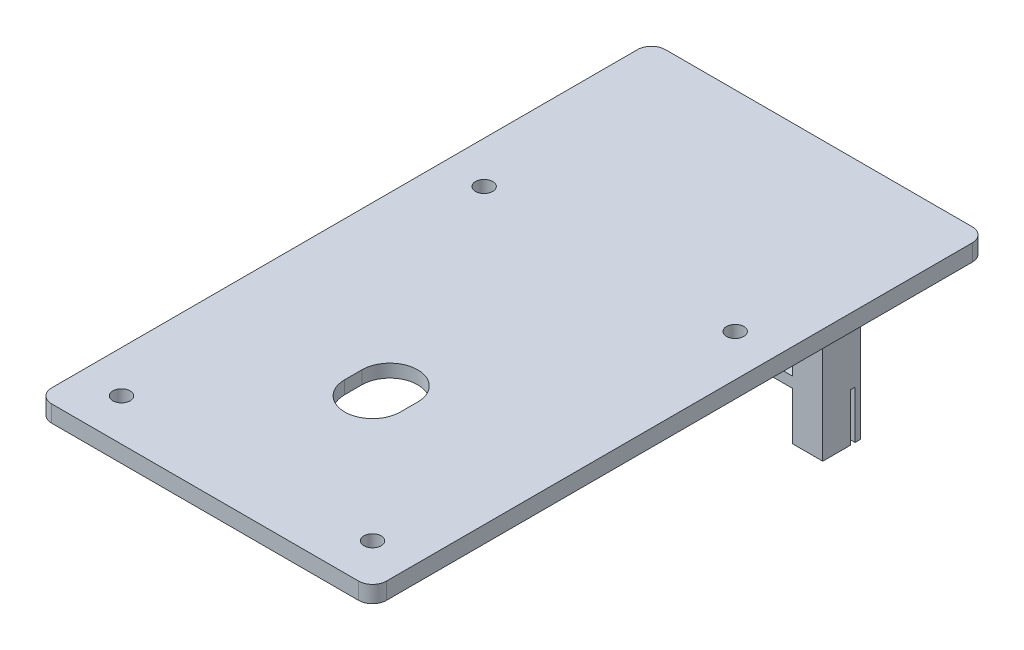
SolidWorks part; units mm, degrees
ref_plane "Front Plane" through (0, 0, 0) normal (0, 0, 1) x (1, 0, 0)
ref_plane "Top Plane" through (0, 0, 0) normal (0, 1, 0) x (1, 0, 0)
ref_plane "Right Plane" through (0, 0, 0) normal (1, 0, 0) x (0, 0, -1)
sketch "Sketch1" plane through (0, 0, 0) normal (0, 1, 0) x (1, 0, 0)
  line L1 (0, 0) -> (60, 0)
  line L2 (0, 0) -> (0, 110)
  line L3 (0, 110) -> (60, 110)
  line L4 (60, 0) -> (60, 110)
  dimension "D1" = 60
  dimension "D2" = 110
extrude "Boss-Extrude1" add sketch "Sketch1" along normal blind 3
sketch "Sketch2" plane through (0, 3, 0) normal (0, 1, 0) x (1, 0, 0)
  line L0 (60, 110) -> (0, 110) construction
  line L1 (0, 110) -> (0, 0) construction
  line L2 (60, 0) -> (60, 110) construction
  line L3 (0, 0) -> (60, 0) construction
  circle A0 centre (7.5, 7.5) radius 1.55
  circle A1 centre (52.5, 7.5) radius 1.55
  circle A2 centre (7.5, 72.5) radius 1.55
  circle A3 centre (52.5, 72.5) radius 1.55
  dimension "D1" = 3.1
  dimension "D2" = 3.1
  dimension "D3" = 3.1
  dimension "D4" = 3.1
  dimension "D5" = 37.5
  dimension "D7" = 37.5
  dimension "D8" = 7.5
  dimension "D9" = 7.5
  dimension "D10" = 7.5
  dimension "D11" = 7.5
  dimension "D12" = 7.5
  dimension "D6" = 7.5
extrude "Cut-Extrude1" cut sketch "Sketch2" against normal blind 3
sketch "Sketch3" plane through (0, 3, 0) normal (0, 1, 0) x (1, 0, 0)
  line L0 (30, 33.1) -> (30, 30) construction
  line L1 (35, 33.1) -> (35, 30)
  line L2 (25, 33.1) -> (25, 30)
  line L3 (0, 110) -> (0, 0) construction
  line L4 (0, 0) -> (60, 0) construction
  arc A0 (35, 33.1) -> (25, 33.1) centre (30, 33.1) ccw
  arc A1 (25, 30) -> (35, 30) centre (30, 30) ccw
  point P2 (30, 31.55)
  point P9 (0, 0)
  dimension "D2" = 5
  dimension "D1" = 3.1
  dimension "D3" = 25
  dimension "D4" = 30
extrude "Cut-Extrude2" cut sketch "Sketch3" against normal blind 2.33
sketch "Sketch4" plane through (0, 0, 0) normal (0, -1, 0) x (1, 0, 0)
  line L0 (26.98, -20.0513) -> (33.02, -20.0513)
  line L1 (40.32, -27.3513) -> (40.32, -35.65)
  line L2 (33.02, -42.95) -> (26.98, -42.9307)
  line L3 (19.68, -27.3513) -> (19.7034, -35.6513)
  line L4 (35, -30) -> (35, -33.1) construction
  arc A0 (33.02, -20.0513) -> (40.32, -27.3513) centre (33.02, -27.3513) cw
  arc A1 (40.32, -35.65) -> (33.02, -42.95) centre (33.02, -35.65) cw
  arc A2 (26.98, -20.0513) -> (19.68, -27.3513) centre (26.98, -27.3513) ccw
  arc A3 (19.7034, -35.6513) -> (26.98, -42.9307) centre (27.0034, -35.6307) ccw
  dimension "D2" = 7.3
  dimension "D6" = 7.3
  dimension "D9" = 7.3
  dimension "D12" = 7.3
  dimension "D1" = 6.04
  dimension "D3" = 0
  dimension "D4" = 0
  dimension "D7" = 0
  dimension "D8" = 0
  dimension "D10" = 0
  dimension "D11" = 0
  dimension "D13" = 6.04
  dimension "D14" = 8.3
  dimension "D15" = 5.32
  dimension "D16" = 2.55
  dimension "D17" = 2.6487
extrude "Cut-Extrude3" cut sketch "Sketch4" against normal up to vertex (0.67 mm away)
sketch "Sketch5" plane through (0, 0, 0) normal (0, -1, 0) x (1, 0, 0)
  line L0 (0, -110) -> (0, 0) construction
  line L1 (60, 0) -> (60, -110) construction
  line L2 (60, -110) -> (0, -110) construction
  circle A0 centre (20.05, -102.5) radius 1.375
  circle A1 centre (39.95, -102.5) radius 1.375
  circle A2 centre (39.95, -76.3) radius 1.375
  circle A3 centre (20.05, -76.3) radius 1.375
  dimension "D1" = 2.75
  dimension "D2" = 2.75
  dimension "D3" = 2.75
  dimension "D4" = 2.75
  dimension "D5" = 0
  dimension "D6" = 19.9
  dimension "D7" = 0
  dimension "D8" = 19.9
  dimension "D9" = 0
  dimension "D10" = 26.2
  dimension "D11" = 20.05
  dimension "D12" = 20.05
  dimension "D13" = 7.5
sketch "Sketch6" plane through (0, 0, 0) normal (0, -1, 0) x (1, 0, 0)
  line L0 (51.3, -93.2) -> (52.5, -93.2)
  line L2 (48.3, -93.2) -> (48.3, -94)
  line L4 (51.3, -93.2) -> (51.3, -94)
  line L5 (52.5, -94) -> (51.3, -94)
  line L6 (52.5, -94) -> (52.5, -95)
  line L7 (52.5, -95) -> (47.1, -95)
  line L8 (47.1, -94) -> (47.1, -95)
  line L9 (47.1, -88.2) -> (52.5, -88.2)
  line L10 (47.1, -88.2) -> (47.1, -93.2)
  line L11 (47.1, -93.2) -> (48.3, -93.2)
  line L12 (52.5, -88.2) -> (52.5, -93.2)
  line L13 (48.3, -94) -> (47.1, -94)
  line L14 (60, 0) -> (60, -110) construction
  line L15 (11.7, -93.2) -> (12.9, -93.2)
  line L16 (8.7, -93.2) -> (8.7, -94)
  line L17 (11.7, -93.2) -> (11.7, -94)
  line L18 (12.9, -94) -> (11.7, -94)
  line L19 (12.9, -94) -> (12.9, -95)
  line L20 (12.9, -95) -> (7.5, -95)
  line L21 (7.5, -94) -> (7.5, -95)
  line L22 (7.5, -88.2) -> (12.9, -88.2)
  line L23 (7.5, -88.2) -> (7.5, -93.2)
  line L24 (7.5, -93.2) -> (8.7, -93.2)
  line L25 (12.9, -88.2) -> (12.9, -93.2)
  line L26 (8.7, -94) -> (7.5, -94)
  line L27 (0, -110) -> (0, 0) construction
  line L28 (60, -110) -> (0, -110) construction
  dimension "D11" = 3
  dimension "D1" = 3
  dimension "D2" = 1.2
  dimension "D3" = 1.2
  dimension "D4" = 1
  dimension "D5" = 0.8
  dimension "D6" = 5
  dimension "D7" = 7.5
  dimension "D8" = 5.4
  dimension "D9" = 3
  dimension "D10" = 5.4
  dimension "D12" = 1.2
  dimension "D13" = 0.8
  dimension "D14" = 5
  dimension "D15" = 5.4
  dimension "D16" = 3
  dimension "D17" = 5.4
  dimension "D18" = 7.5
  dimension "D19" = 7.5
  dimension "D20" = 0
  dimension "D21" = 0
  dimension "D22" = 15
extrude "Boss-Extrude3" add sketch "Sketch6" along normal blind 25
sketch "Sketch8" plane through (0, 0, 0) normal (0, -1, 0) x (1, 0, 0)
  line L0 (24.5866, -74) -> (36.7285, -74)
  line L1 (60, -110) -> (0, -110) construction
  dimension "D1" = 36
ref_plane "Plane1" through (0, 0, 0) normal (0, 1, 0) x (1, 0, 0)
ref_plane "Plane2" through (0, -16.5, 0) normal (0, 1, 0) x (1, 0, 0)
sketch "Sketch9" plane through (0, -16.5, 0) normal (0, 1, 0) x (1, 0, 0)
  line L1 (7.5, 95) -> (52.5, 95)
  line L2 (7.5, 95) -> (7.5, 88.2)
  line L3 (7.5, 88.2) -> (52.5, 88.2)
  line L4 (52.5, 95) -> (52.5, 88.2)
extrude "Boss-Extrude4" add sketch "Sketch9" along normal blind 2
sketch "Sketch10" plane through (0, 0, 0) normal (0, -1, 0) x (1, 0, 0)
  line L1 (7.5, -88.2) -> (12.9, -88.2)
  line L2 (7.5, -88.2) -> (7.5, -95)
  line L3 (7.5, -95) -> (12.9, -95)
  line L4 (12.9, -88.2) -> (12.9, -95)
  line L5 (47.1, -88.2) -> (52.5, -88.2)
  line L6 (47.1, -88.2) -> (47.1, -95)
  line L7 (47.1, -95) -> (52.5, -95)
  line L8 (52.5, -88.2) -> (52.5, -95)
extrude "Boss-Extrude5" add sketch "Sketch10" along normal up to vertex (14.5 mm away)
fillet "Fillet1" radius 2.5 4 edges at (60, 1.5, -110) (60, 1.5, 0) (0, 1.5, -110) (0, 1.5, 0)
sketch "Sketch11" plane through (0, 0, 0) normal (0, -1, 0) x (1, 0, 0)
  line L0 (33.02, -20.0513) -> (26.98, -20.0513) construction
  line L1 (26.98, -42.9307) -> (33.02, -42.95) construction
  circle A0 centre (30, -18.5513) radius 0.75
  circle A1 centre (30, -44.9404) radius 0.75
  arc A3 (25, -33.1) -> (35, -33.1) centre (30, -33.1) ccw construction
  arc A4 (35, -30) -> (25, -30) centre (30, -30) ccw construction
  point P4 (26.6966, -18.1198)
  point P5 (28.0323, -46.8117)
  dimension "D1" = 1.5
  dimension "D2" = 1.5
  dimension "D3" = 0
  dimension "D4" = 0
  dimension "D5" = 1.5
  dimension "D6" = 2
extrude "Boss-Extrude6" add sketch "Sketch11" along normal blind 6
sketch "Sketch12" plane through (0, -16.5, 0) normal (0, -1, 0) x (1, 0, 0)
  line L0 (12.9, -94) -> (12.9, -95)
  line L1 (12.9, -88.2) -> (47.1, -88.2)
  line L2 (12.9, -88.2) -> (12.9, -93.2)
  line L3 (12.9, -95) -> (47.1, -95)
  line L4 (47.1, -88.2) -> (47.1, -93.2)
  line L5 (48.3, -93.2) -> (47.1, -93.2)
  line L6 (48.3, -93.2) -> (48.3, -94)
  line L7 (48.3, -94) -> (47.1, -94)
  line L8 (11.7, -93.2) -> (11.7, -94)
  line L9 (47.1, -94) -> (47.1, -95)
  line L10 (12.9, -93.2) -> (11.7, -93.2)
  line L11 (12.9, -94) -> (11.7, -94)
  line L13 (7.5, -93.2) -> (8.7, -93.2)
  line L14 (7.5, -93.2) -> (7.5, -94)
  line L15 (7.5, -94) -> (8.7, -94)
  line L16 (8.7, -93.2) -> (8.7, -94)
  line L17 (52.5, -93.2) -> (51.3, -93.2)
  line L18 (52.5, -93.2) -> (52.5, -94)
  line L19 (52.5, -94) -> (51.3, -94)
  line L20 (51.3, -93.2) -> (51.3, -94)
extrude "Cut-Extrude4" cut sketch "Sketch12" against normal blind 0.1
